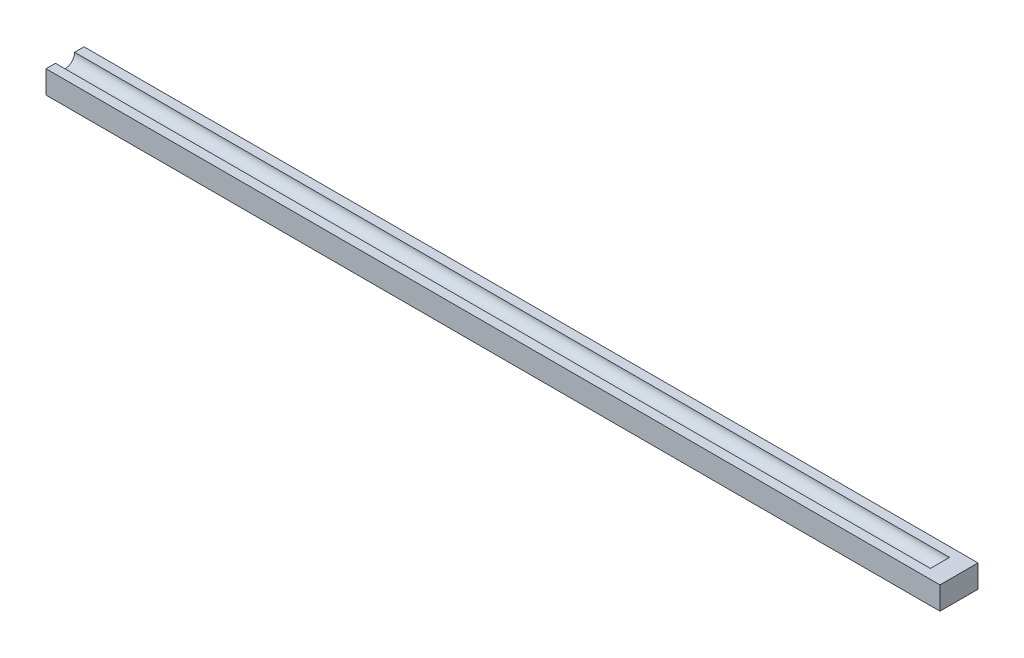
SolidWorks part; units mm, degrees
ref_plane "前视基准面" through (0, 0, 0) normal (0, 0, 1) x (1, 0, 0)
ref_plane "上视基准面" through (0, 0, 0) normal (0, 1, 0) x (1, 0, 0)
ref_plane "右视基准面" through (0, 0, 0) normal (1, 0, 0) x (0, 0, -1)
other "Configuration Table"
sketch "草图1" plane through (0, 0, 0) normal (0, 1, 0) x (1, 0, 0)
  line L1 (0, -5) -> (235, -5)
  line L2 (0, -5) -> (0, 5)
  line L3 (0, 5) -> (235, 5)
  line L4 (235, -5) -> (235, 5)
  point P5 (0, 0)
  point P6 (7.7087, 0)
  dimension "D1" = 235
  dimension "D2" = 10
extrude "凸台-拉伸1" add sketch "草图1" along normal blind 6
sketch "草图4" plane through (0, 0, 0) normal (-1, 0, 0) x (0, 0, 1)
  line L0 (-5, 6) -> (5, 6) construction
  circle A0 centre (0, 6) radius 2.515
  dimension "D1" = 5.03
extrude "切除-拉伸1" cut sketch "草图4" against normal blind 230
